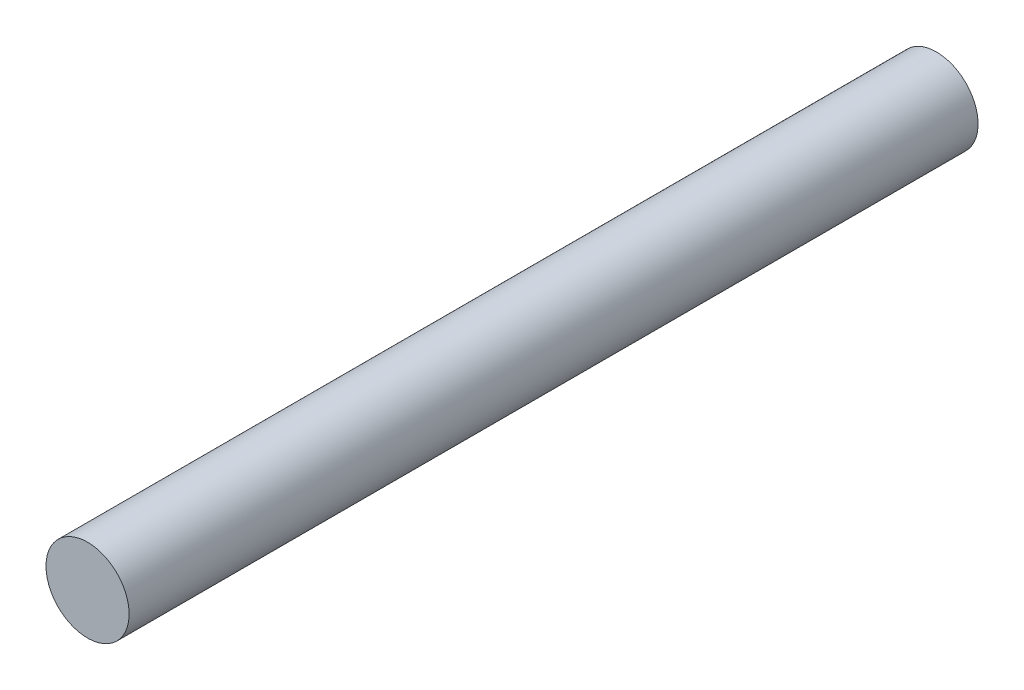
SolidWorks part; units mm, degrees
ref_plane "Front Plane" through (0, 0, 0) normal (0, 0, 1) x (1, 0, 0)
ref_plane "Top Plane" through (0, 0, 0) normal (0, 1, 0) x (1, 0, 0)
ref_plane "Right Plane" through (0, 0, 0) normal (1, 0, 0) x (0, 0, -1)
sketch "Sketch1" plane through (0, 0, 0) normal (0, 0, 1) x (1, 0, 0)
  circle A0 centre (0, 0) radius 4.7625
  dimension "D1" = 9.525
extrude "Boss-Extrude1" add sketch "Sketch1" along normal blind 97.282
equation "\"Wheel Thickness\"= 1in"
equation "\"Wheel Diameter\"= 3in"
equation "\"Motor Rear Diameter\" = 36.2mm"
equation "\"Motor Front Diameter\" = 12mm"
equation "\"Material Thickness\" = .25in"
equation "\"Wheel Cutout Diameter\"= 2cm"
equation "\"Motor Mount Tab Thickness\" = 100mm"
equation "\"Motor Mount Tab Height\" = 40mm"
equation "\"Motor Shaft Diameter\" = 3mm"
equation "\"Wheel Radius Clearance\" = 5mm"
equation "\"Wheel Cutout Width\" = 1.5in"
equation "\"Base Diameter\" = 10in"
equation "\"Wheel Mount Distance\" = 5mm"
equation "\"Motor Mount Distance\" = 50mm"
equation "\"Motor Cutout Length\" = 6in"
equation "\"Motor Cutout Height\" = 2in "
equation "\"Rod Diameter\" = 3/8in"
equation "\"Rod Length\" = 1in"
equation "\"Barrel Front Length\" = 1.8in"
equation "\"Barrerl Rear Length\" = 5in "
equation "\"Barrel Fillet Radius\" = 1in "
equation "\"Barrel Angle\" = 25deg"
equation "\"Barrel Diameter\" = 50mm"
equation "\"Barrel Shell Width\" = 2mm"
equation "\"Second Level Diameter\" = 10in"
equation "\"Ball Diameter\" = 40mm"
equation "\"Third Level Length\" = 9in"
equation "\"Third Level Height\" = 9in"
equation "\"Barrel Tab Clearance\" = 5mm"
equation "\"Barrel Tab Distance Away\" = 2mm"
equation "\"Hole Distance Apart\" = 2.8in"
equation "\"Barrel Tab Distance\"= 1.5in "
equation "\"Third Level Rod Distance\" = .5in"
equation " \"Second Rod Diameter\" = 3/8in"
equation "\"Second Rod Length\" = 3.88in"
equation "\"Bumper Wheel Clearance\" = 1.2in"
equation "\"Servo Tab Height\" = 4in"
equation "\"Servo Tab Width\" = 2in"
equation "\"Servo Tab Hole Horizontal Distance\" = 1in"
equation "\"Servo Tab Hole Vertical Distance\" = 1.5in "
equation "\"Servo Hole Vertical Distance\" = 3in"
equation "\"Servo Hole Diameter\" = 1/4in"
equation "\"Servo Hole Shaft Length\" = 1.45in"
equation "\"Third Rod Length\" = 3.83in"
equation "\"Third Rod Diameter\" = 3/8in"
equation "\"Third Rod Radius Distance\" = 2in"
equation "\"Third Rod Angle Distance\" = 45deg"
equation "\"Fourth Level Diameter\" = 3.5in"
equation "\"D1@Sketch1\"=\"Third Rod Diameter\""
equation "\"D1@Boss-Extrude1\"=\"Third Rod Length\""
